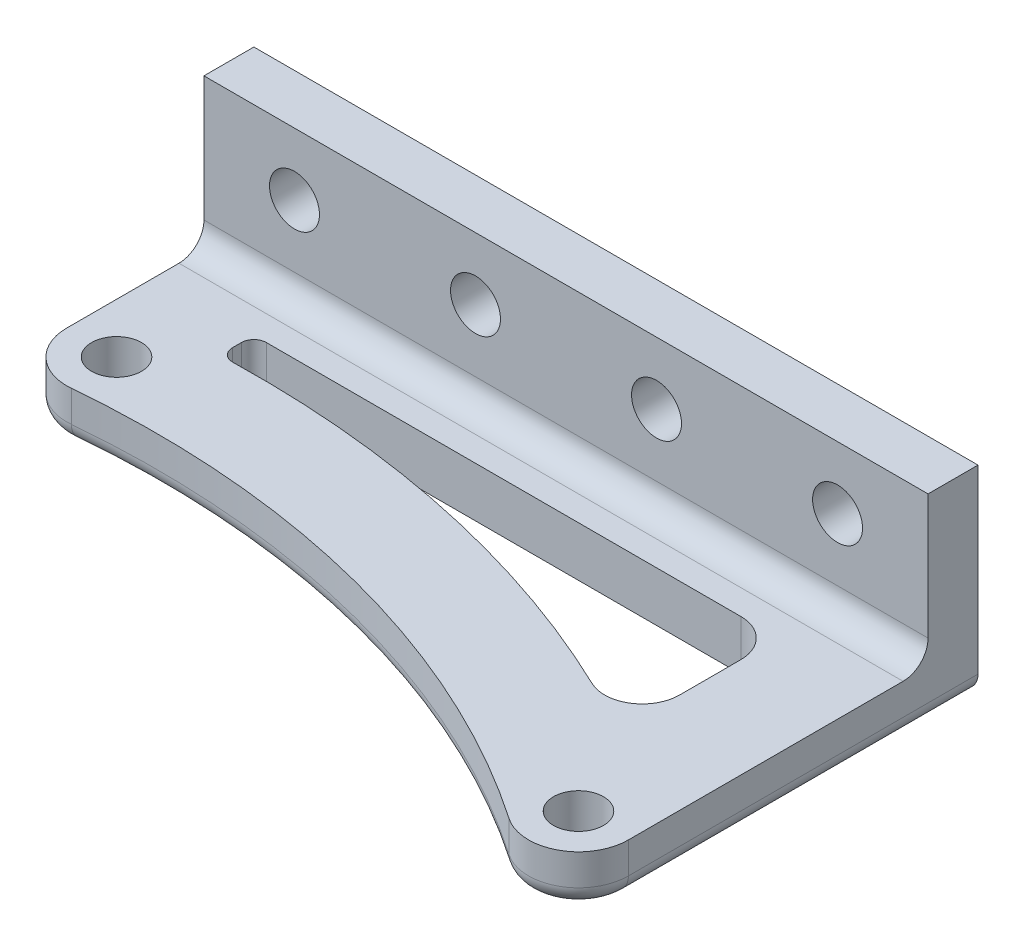
SolidWorks part; units mm, degrees
ref_plane "Front Plane" through (0, 0, 0) normal (0, 0, 1) x (1, 0, 0)
ref_plane "Top Plane" through (0, 0, 0) normal (0, 1, 0) x (1, 0, 0)
ref_plane "Right Plane" through (0, 0, 0) normal (1, 0, 0) x (0, 0, -1)
sketch "Sketch1" plane through (0, 0, 0) normal (0, 1, 0) x (1, 0, 0)
  line L3 (-4, 13) -> (-4, 28)
  line L4 (-4, 28) -> (54, 28)
  line L5 (54, 28) -> (54, 0)
  line L6 (4, 18.2898) -> (4, 19)
  line L7 (46, 12.0969) -> (46, 17)
  line L9 (25, 20) -> (43, 20)
  line L10 (25, 20) -> (5, 20)
  circle A0 centre (0, 13) radius 2
  circle A1 centre (50, 0) radius 2
  arc A4 (-4, 13) -> (0.361, 9.0163) centre (0, 13) ccw
  arc A5 (47.7444, -3.3033) -> (0.361, 9.0163) centre (6.8983, -63.1218) ccw
  arc A7 (47.7444, -3.3033) -> (54, 0) centre (50, 0) ccw
  arc A10 (5.0233, 17.2901) -> (4, 18.2898) centre (5, 18.2898) cw
  arc A11 (5, 20) -> (4, 19) centre (5, 19) ccw
  arc A12 (46, 12.0969) -> (41.7019, 9.3923) centre (43, 12.0969) cw
  arc A13 (41.7019, 9.3923) -> (5.0233, 17.2901) centre (6.8983, -63.1218) ccw
  arc A14 (46, 17) -> (43, 20) centre (43, 17) ccw
  point P0 (10.2047, -50.4051)
  point P6 (10.2047, -50.4051)
  point P7 (76.4257, -50.4051)
  point P9 (10.2047, 11.8159)
  point P12 (87.3321, -63.1218)
  point P25 (6.8983, 9.3119)
  dimension "D1" = 1
  dimension "D2" = 3
extrude "Boss-Extrude1" add sketch "Sketch1" along normal blind 4
sketch "Sketch2" plane through (0, 4, 0) normal (0, 1, 0) x (1, 0, 0)
  line L0 (-4, 28) -> (-4, 24)
  line L1 (-4, 28) -> (-4, 13) construction
  line L2 (-4, 24) -> (54, 24)
  line L3 (54, 0) -> (54, 28) construction
  line L4 (54, 24) -> (54, 28)
  line L5 (54, 28) -> (-4, 28)
extrude "Boss-Extrude2" add sketch "Sketch2" along normal blind 12
fillet "Fillet2" radius 2 1 edges at (25, 4, -24)
fillet "Fillet4" radius 1.5 5 edges at (-4, 0, -20.5) (54, 0, -14) (51.8678, 0, 3.5371) (25.1251, 0, -6.9812) (-2.6978, 0, -10.0467)
sketch "Sketch4" plane through (0, 0, -24) normal (0, 0, 1) x (1, 0, 0)
  circle A0 centre (3.25, 11) radius 2
  circle A1 centre (17.75, 11) radius 2
  circle A2 centre (32.25, 11) radius 2
  circle A3 centre (46.75, 11) radius 2
extrude "Cut-Extrude1" cut sketch "Sketch4" against normal up to surface (4 mm away) contours A1 | A2 | A3 | A0 up to face at (25, 5.7298, -28)
